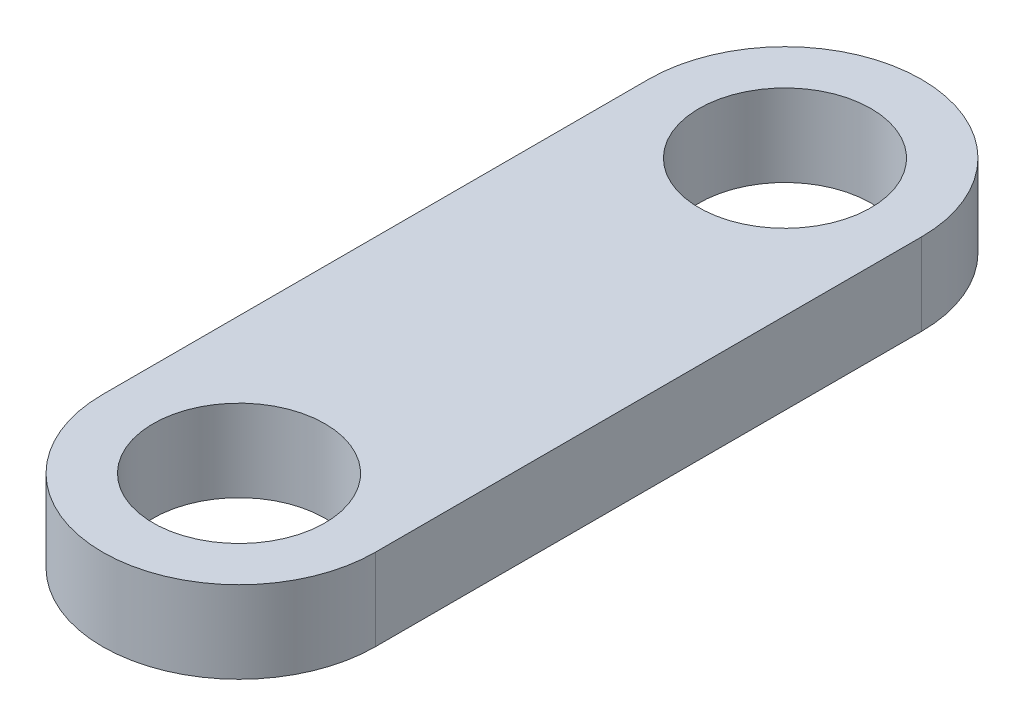
SolidWorks part; units mm, degrees
material "6061-T6 (SS)"
ref_plane "X-Y Datum" through (0, 0, 0) normal (0, 0, 1) x (1, 0, 0)
ref_plane "X-Z Datum" through (0, 0, 0) normal (0, 1, 0) x (1, 0, 0)
ref_plane "Y-Z Datum" through (0, 0, 0) normal (1, 0, 0) x (0, 0, -1)
sketch "Sketch2" plane through (0, 0, 0) normal (0, 1, 0) x (1, 0, 0)
  line L7 (3.175, 0) -> (3.175, -12.7)
  line L8 (-3.175, 0) -> (-3.175, -12.7)
  circle A0 centre (0, 0) radius 2
  arc A2 (-3.175, 0) -> (3.175, 0) centre (0, 0) cw
  arc A3 (3.175, -12.7) -> (-3.175, -12.7) centre (0, -12.7) cw
  circle A4 centre (0, -12.7) radius 2
  dimension "D3" = 6.35
  dimension "D1" = 4
  dimension "D5" = 4
  dimension "D4" = 12.7
extrude "Boss-Extrude1" add sketch "Sketch2" along normal blind 1.905
